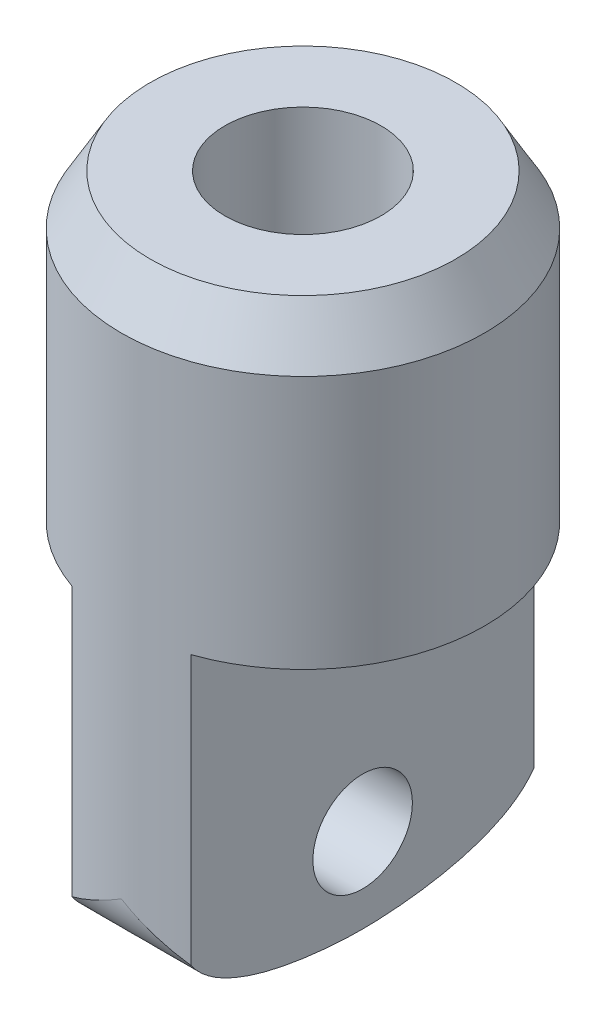
SolidWorks part; units mm, degrees
ref_plane "Front" through (0, 0, 0) normal (0, 0, 1) x (1, 0, 0)
ref_plane "Top" through (0, 0, 0) normal (0, 1, 0) x (1, 0, 0)
ref_plane "Right" through (0, 0, 0) normal (1, 0, 0) x (0, 0, -1)
sketch "Sketch3" plane through (0, 0, 0) normal (0, 1, 0) x (1, 0, 0)
  circle A0 centre (0, 0) radius 4.6355
  dimension "D1" = 9.271
extrude "Boss-Extrude1" add sketch "Sketch3" along normal mid plane 16.002
sketch "Sketch4" plane through (0, 8.001, 0) normal (0, 1, 0) x (1, 0, 0)
  circle A0 centre (0, 0) radius 1.9939
  dimension "D1" = 3.9878
extrude "Cut-Extrude1" cut sketch "Sketch4" against normal blind 5.588
chamfer "Chamfer1" distance 1.27 angle 30 1 edges at (0, 8.001, 4.6355)
sketch "Sketch5" plane through (0, 0, 0) normal (0, 0, 1) x (1, 0, 0)
  line L0 (0, 0) -> (0, -8.001) construction
  line L1 (-4.6355, -8.001) -> (4.6355, -8.001) construction
  line L2 (-5.4117, -8.001) -> (-5.4117, 0.254)
  line L3 (1.524, -8.001) -> (5.4117, -8.001)
  line L4 (1.524, -8.001) -> (1.524, 0.254)
  line L5 (1.524, 0.254) -> (5.4117, 0.254)
  line L6 (5.4117, -8.001) -> (5.4117, 0.254)
  line L7 (-1.524, 0.254) -> (-5.4117, 0.254)
  line L8 (-1.524, -8.001) -> (-1.524, 0.254)
  line L9 (-1.524, -8.001) -> (-5.4117, -8.001)
  dimension "D1" = 1.524
  dimension "D2" = 8.255
extrude "Cut-Extrude2" cut sketch "Sketch5" against normal up to next and the other way up to next
sketch "Sketch6" plane through (1.524, 0, 0) normal (1, 0, 0) x (0, 0, -1)
  line L0 (-4.6355, 6.731) -> (-4.6355, -8.001) construction
  line L1 (-4.3778, -8.001) -> (4.3778, -8.001) construction
  line L2 (0, 0) -> (0, -8.001) construction
  line L3 (-4.6355, -10.7557) -> (-4.6355, -1.1954) construction
  line L5 (-4.6355, -5.7767) -> (4.6355, -5.7767)
  line L6 (-4.6355, -5.7767) -> (-4.6355, -10.7557)
  line L7 (-4.6355, -5.7767) -> (-4.6355, -8.001)
  line L8 (-4.6355, -8.001) -> (4.6355, -8.001)
  line L9 (4.6355, -5.7767) -> (4.6355, -8.001)
  spline S0 degree 3 poles (-4.6355, -5.7767) (-4.6355, -7.8516) (-0.7888, -8.001) (0, -8.001) knots 0 0 0 0 1 1 1 1
  spline S1 degree 3 poles (4.6355, -5.7767) (4.6355, -7.8516) (0.7888, -8.001) (0, -8.001) knots 0 0 0 0 1 1 1 1
extrude "Cut-Extrude3" cut sketch "Sketch6" against normal up to next
sketch "Sketch7" plane through (1.524, 0, 0) normal (1, 0, 0) x (0, 0, -1)
  line L0 (-4.3778, 0.254) -> (4.3778, 0.254) construction
  circle A0 centre (0, -5.842) radius 1.27
  point P4 (0, 0)
  dimension "D1" = 2.54
  dimension "D2" = 6.096
extrude "Cut-Extrude4" cut sketch "Sketch7" against normal up to next
